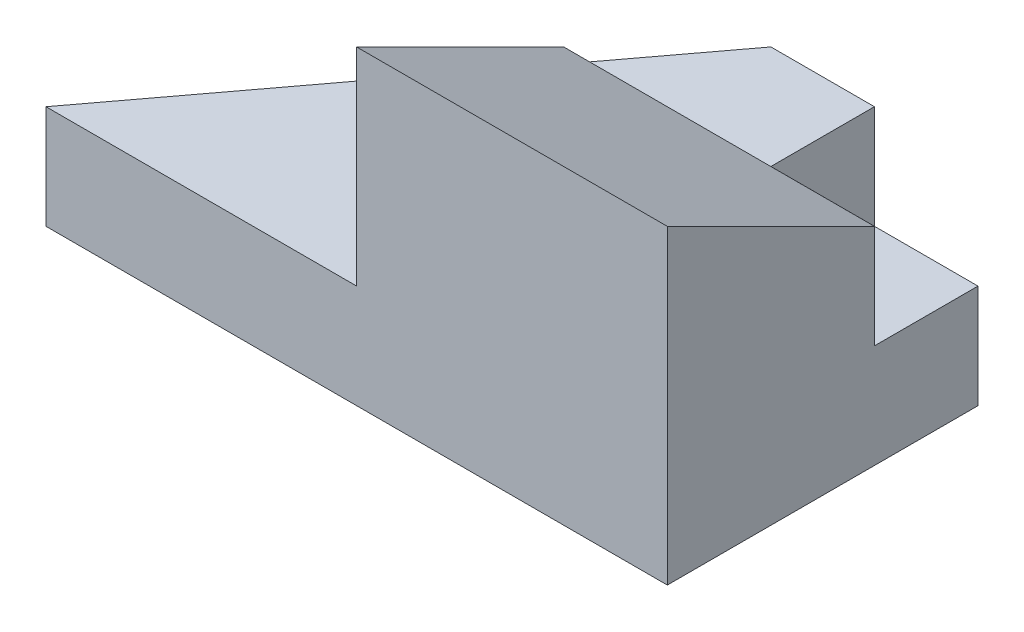
SolidWorks part; units mm, degrees
ref_plane "Front Plane" through (0, 0, 0) normal (0, 0, 1) x (1, 0, 0)
ref_plane "Top Plane" through (0, 0, 0) normal (0, 1, 0) x (1, 0, 0)
ref_plane "Right Plane" through (0, 0, 0) normal (1, 0, 0) x (0, 0, -1)
sketch "Sketch1" plane through (0, 0, 0) normal (0, 0, 1) x (1, 0, 0)
  line L1 (0, 0) -> (-1524, 0)
  line L2 (0, 0) -> (0, 762)
  line L3 (0, 762) -> (-1524, 762)
  line L4 (-1524, 0) -> (-1524, 762)
  dimension "D1" = 762
  dimension "D2" = 1524
extrude "Boss-Extrude1" add sketch "Sketch1" along normal blind 1016 contours L3 L4 L1 L2
ref_plane "Plane1" through (-1524, 762, 0) normal (-1, 0, 0) x (0, 0, 1)
sketch "Sketch3" plane through (0, 0, 0) normal (0, 0, -1) x (-1, 0, 0)
  line L1 (1524, 762) -> (762, 762)
  line L2 (1524, 762) -> (1524, 254.1216)
  line L3 (1524, 254.1216) -> (762, 254.1216)
  line L4 (762, 762) -> (762, 254.1216)
extrude "Cut-Extrude1" cut sketch "Sketch3" against normal blind 1016
sketch "Sketch5" plane through (0, 254.1216, 0) normal (0, 1, 0) x (1, 0, 0)
  line L0 (-1524, -1016) -> (-762, 0)
  line L1 (-762, 0) -> (-1524, 0)
  line L2 (-762, 0) -> (-1524, 0) construction
  line L3 (-1524, -1016) -> (-1524, 0) construction
  line L4 (-1524, 0) -> (-1524, -1016)
extrude "Cut-Extrude2" cut sketch "Sketch5" against normal blind 260.604
sketch "Sketch6" plane through (-762, 0, 0) normal (-1, 0, 0) x (0, 0, 1)
  line L0 (1016, 762) -> (0, 762) construction
  line L1 (0, 254.1216) -> (254, 254.1216)
  line L2 (0, 254.1216) -> (0, 762)
  line L3 (0, 762) -> (254, 762)
  line L4 (254, 254.1216) -> (254, 762)
  dimension "D1" = 254
extrude "Cut-Extrude3" cut sketch "Sketch6" against normal blind 1081.278
sketch "Sketch7" plane through (-762, 0, 0) normal (-1, 0, 0) x (0, 0, 1)
  line L1 (254, 254.1216) -> (508, 254.1216)
  line L2 (254, 254.1216) -> (254, 762.1216)
  line L3 (254, 762.1216) -> (508, 762.1216)
  line L4 (508, 254.1216) -> (508, 762.1216)
  dimension "D1" = 254
  dimension "D2" = 508
extrude "Cut-Extrude4" cut sketch "Sketch7" against normal blind 1081.278
sketch "Sketch8" plane through (0, 254.1216, 0) normal (0, 1, 0) x (1, 0, 0)
  line L1 (0, 0) -> (-508.046, 0)
  line L2 (0, 0) -> (0, -254)
  line L3 (0, -254) -> (-508.046, -254)
  line L4 (-508.046, 0) -> (-508.046, -254)
  dimension "D1" = 508.046
  dimension "D2" = 254
extrude "Cut-Extrude5" cut sketch "Sketch8" against normal blind 1081.278
sketch "Sketch10" plane through (-762, 0, 0) normal (-1, 0, 0) x (0, 0, 1)
  line L0 (1016, 762) -> (508, 762)
  line L1 (508, 762) -> (508, 508.0608)
  line L2 (508, 254.1216) -> (508, 762) construction
  line L3 (508, 508.0608) -> (1016, 762)
extrude "Cut-Extrude6" cut sketch "Sketch10" against normal blind 835.406
